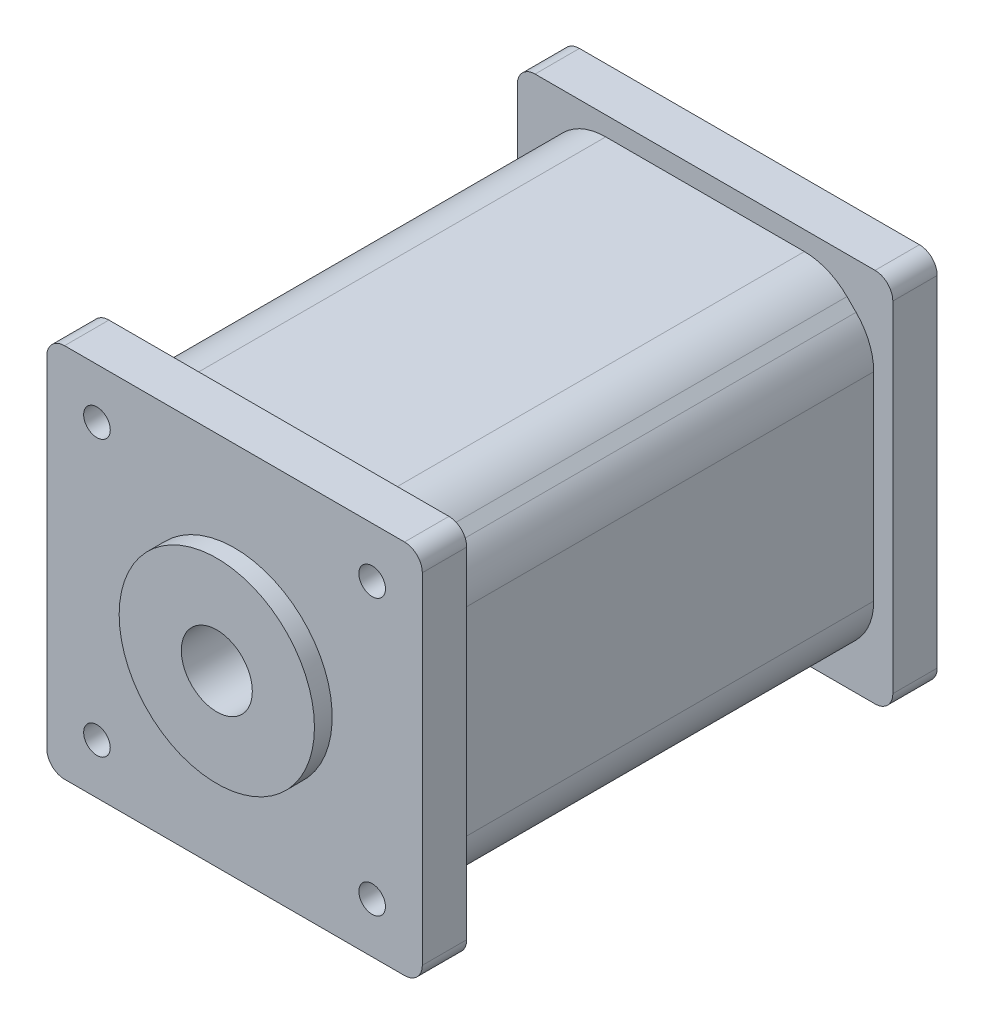
SolidWorks part; units mm, degrees
material "氧化铝"
ref_plane "前视基准面" through (0, 0, 0) normal (0, 0, 1) x (1, 0, 0)
ref_plane "上视基准面" through (0, 0, 0) normal (0, 1, 0) x (1, 0, 0)
ref_plane "右视基准面" through (0, 0, 0) normal (1, 0, 0) x (0, 0, -1)
sketch "草图1" plane through (0, 0, 0) normal (0, 0, 1) x (1, 0, 0)
  line L1 (-19.15, -21.15) -> (19.15, -21.15)
  line L2 (-21.15, -19.15) -> (-21.15, 19.15)
  line L3 (-19.15, 21.15) -> (19.15, 21.15)
  line L4 (21.15, -19.15) -> (21.15, 19.15)
  line L5 (-21.15, -21.15) -> (21.15, 21.15) construction
  line L6 (-21.15, 21.15) -> (21.15, -21.15) construction
  arc A0 (-21.15, 19.15) -> (-19.15, 21.15) centre (-19.15, 19.15) cw
  arc A1 (21.15, -19.15) -> (19.15, -21.15) centre (19.15, -19.15) cw
  arc A2 (19.15, 21.15) -> (21.15, 19.15) centre (19.15, 19.15) cw
  arc A3 (-21.15, -19.15) -> (-19.15, -21.15) centre (-19.15, -19.15) ccw
  point P0 (0, 0)
  dimension "D1" = 2
  dimension "D4" = 2
  dimension "D5" = 2
  dimension "D6" = 2
  dimension "D2" = 42.3
  dimension "D3" = 42.3
extrude "凸台-拉伸1" add sketch "草图1" along normal blind 5 contours L2 A0 L3 A2 L4 A1 L1 A3
sketch "草图2" plane through (0, 0, 5) normal (0, 0, 1) x (1, 0, 0)
  line L0 (-17.0116, 15.9884) -> (-15.9884, 17.0116)
  line L1 (-11.1879, -19) -> (11.1879, -19)
  line L2 (-19, -11.1879) -> (-19, 11.1879)
  line L3 (-11.1879, 19) -> (11.1879, 19)
  line L4 (19, -11.1879) -> (19, 11.1879)
  line L5 (-19, -19) -> (19, 19) construction
  line L6 (-19, 19) -> (19, -19) construction
  line L7 (-15.9884, -17.0116) -> (-17.0116, -15.9884)
  line L8 (15.9884, -17.0116) -> (17.0116, -15.9884)
  line L9 (15.9884, 17.0116) -> (17.0116, 15.9884)
  arc A0 (11.1879, 19) -> (15.9884, 17.0116) centre (11.1879, 12.2111) cw
  arc A1 (17.0116, 15.9884) -> (19, 11.1879) centre (12.2111, 11.1879) cw
  arc A2 (19, -11.1879) -> (17.0116, -15.9884) centre (12.2111, -11.1879) cw
  arc A3 (15.9884, -17.0116) -> (11.1879, -19) centre (11.1879, -12.2111) cw
  arc A4 (-11.1879, -19) -> (-15.9884, -17.0116) centre (-11.1879, -12.2111) cw
  arc A5 (-17.0116, -15.9884) -> (-19, -11.1879) centre (-12.2111, -11.1879) cw
  arc A6 (-17.0116, 15.9884) -> (-19, 11.1879) centre (-12.2111, 11.1879) ccw
  arc A7 (-11.1879, 19) -> (-15.9884, 17.0116) centre (-11.1879, 12.2111) ccw
  point P0 (0, 0)
  point P16 (14, 19)
  point P19 (19, 14)
  point P22 (19, -14)
  point P25 (14, -19)
  point P28 (-14, -19)
  point P31 (-19, -14)
  point P34 (-19, 14)
  point P37 (-14, 19)
  dimension "D3" = 6.7889
  dimension "D1" = 38
  dimension "D2" = 38
extrude "凸台-拉伸2" add sketch "草图2" along normal blind 48
sketch "草图3" plane through (0, 0, 53) normal (0, 0, 1) x (1, 0, 0)
  line L1 (-19.15, -21.15) -> (19.15, -21.15)
  line L2 (-21.15, -19.15) -> (-21.15, 19.15)
  line L3 (-19.15, 21.15) -> (19.15, 21.15)
  line L4 (21.15, -19.15) -> (21.15, 19.15)
  line L5 (-21.15, -21.15) -> (21.15, 21.15) construction
  line L6 (-21.15, 21.15) -> (21.15, -21.15) construction
  arc A0 (19.15, 21.15) -> (21.15, 19.15) centre (19.15, 19.15) cw
  arc A1 (21.15, -19.15) -> (19.15, -21.15) centre (19.15, -19.15) cw
  arc A2 (-19.15, -21.15) -> (-21.15, -19.15) centre (-19.15, -19.15) cw
  arc A3 (-19.15, 21.15) -> (-21.15, 19.15) centre (-19.15, 19.15) ccw
  point P0 (0, 0)
  dimension "D3" = 2
  dimension "D1" = 42.3
  dimension "D2" = 42.3
extrude "凸台-拉伸4" add sketch "草图3" along normal blind 5
sketch "草图4" plane through (0, 0, 58) normal (0, 0, 1) x (1, 0, 0)
  circle A0 centre (15.5, 15.5) radius 1.5
  circle A1 centre (15.5, -15.5) radius 1.5
  circle A2 centre (-15.5, -15.5) radius 1.5
  circle A3 centre (-15.5, 15.5) radius 1.5
  dimension "D1" = 4
extrude "切除-拉伸1" cut sketch "草图4" against normal blind 4.5
sketch "草图5" plane through (0, 0, 58) normal (0, 0, 1) x (1, 0, 0)
  circle A0 centre (0, 0) radius 11
extrude "凸台-拉伸5" add sketch "草图5" along normal blind 2
sketch "草图6" plane through (0, 0, 60) normal (0, 0, 1) x (1, 0, 0)
  circle A0 centre (0, 0) radius 4
extrude "切除-拉伸2" cut sketch "草图6" against normal blind 20
